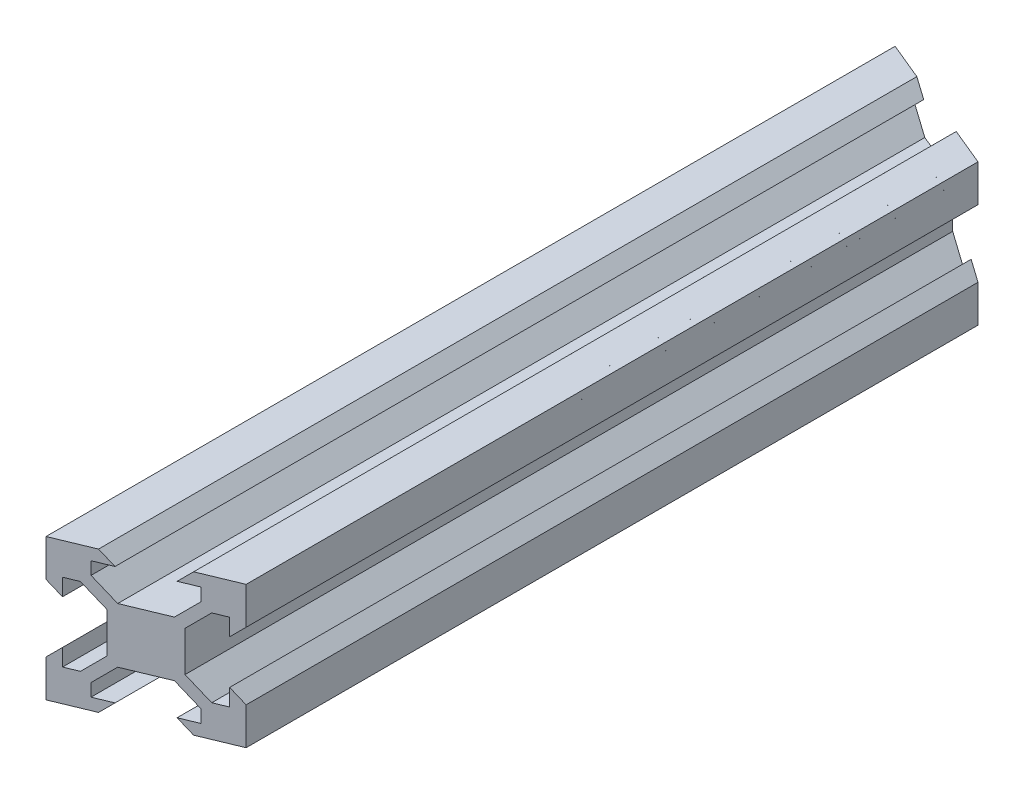
SolidWorks part; units mm, degrees
material "6061 Alloy"
ref_plane "Front Plane" through (0, 0, 0) normal (0, 0, 1) x (1, 0, 0)
ref_plane "Top Plane" through (0, 0, 0) normal (0, 1, 0) x (1, 0, 0)
ref_plane "Right Plane" through (0, 0, 0) normal (1, 0, 0) x (0, 0, -1)
sketch "Sketch1" plane through (0, 0, 0) normal (0, 0, 1) x (1, 0, 0)
  line L4 (-2.8343, 3.894) -> (2.8343, 3.894)
  line L6 (2.8343, 3.894) -> (5.5, 6.5588)
  line L7 (5.5, 6.5588) -> (5.5, 8.3491)
  line L8 (5.5, 8.3491) -> (3.1, 8.3491)
  line L11 (3.1, 8.3491) -> (4.75, 9.9986)
  line L12 (4.75, 9.9986) -> (10, 9.9986)
  line L14 (10, 9.9986) -> (10, 4.747)
  line L16 (10, 4.747) -> (8.35, 3.0975)
  line L17 (8.35, 3.0975) -> (8.3507, 5.4975)
  line L18 (8.3507, 5.4975) -> (6.5605, 5.498)
  line L19 (6.5605, 5.498) -> (3.8948, 2.8332)
  line L20 (3.8948, 2.8332) -> (3.8948, -2.8332)
  line L22 (-10, 9.9986) -> (-10, 4.747)
  line L23 (-3.8948, 2.8332) -> (-3.8948, -2.8332)
  line L24 (-6.5605, 5.498) -> (-3.8948, 2.8332)
  line L25 (-8.3507, 5.4975) -> (-6.5605, 5.498)
  line L26 (-8.35, 3.0975) -> (-8.3507, 5.4975)
  line L27 (-10, 4.747) -> (-8.35, 3.0975)
  line L28 (-4.75, 9.9986) -> (-10, 9.9986)
  line L29 (-3.1, 8.3491) -> (-4.75, 9.9986)
  line L30 (-5.5, 8.3491) -> (-3.1, 8.3491)
  line L31 (-5.5, 6.5588) -> (-5.5, 8.3491)
  line L32 (-2.8343, 3.894) -> (-5.5, 6.5588)
  line L33 (-2.8343, -3.894) -> (-5.5, -6.5588)
  line L34 (-5.5, -6.5588) -> (-5.5, -8.3491)
  line L35 (-5.5, -8.3491) -> (-3.1, -8.3491)
  line L36 (-3.1, -8.3491) -> (-4.75, -9.9986)
  line L37 (-4.75, -9.9986) -> (-10, -9.9986)
  line L38 (-10, -4.747) -> (-8.35, -3.0975)
  line L39 (-8.35, -3.0975) -> (-8.3507, -5.4975)
  line L40 (-8.3507, -5.4975) -> (-6.5605, -5.498)
  line L41 (-6.5605, -5.498) -> (-3.8948, -2.8332)
  line L42 (-10, -9.9986) -> (-10, -4.747)
  line L43 (6.5605, -5.498) -> (3.8948, -2.8332)
  line L44 (8.3507, -5.4975) -> (6.5605, -5.498)
  line L45 (8.35, -3.0975) -> (8.3507, -5.4975)
  line L46 (10, -4.747) -> (8.35, -3.0975)
  line L47 (10, -9.9986) -> (10, -4.747)
  line L48 (4.75, -9.9986) -> (10, -9.9986)
  line L49 (3.1, -8.3491) -> (4.75, -9.9986)
  line L50 (5.5, -8.3491) -> (3.1, -8.3491)
  line L51 (5.5, -6.5588) -> (5.5, -8.3491)
  line L52 (2.8343, -3.894) -> (5.5, -6.5588)
  line L53 (-2.8343, -3.894) -> (2.8343, -3.894)
  circle A0 centre (0, 0) radius 2.1
  point P52 (0, 3.894)
  point P53 (-3.8948, 0)
  point P54 (3.8948, 0)
  point P74 (0, -3.894)
extrude "Boss-Extrude1" add sketch "Sketch1" along normal blind 120 contours L14 L16 L17 L18 L19 L20 L43 L44 L45 L46 L47 L48 L49 L50 L51 L52 L53 L33 L34 L35 L36 L37 L42 L38 L39 L40 L41 L23 L24 L25 L26 L27 L22 L28 L29 L30 L31 L32 L4 L6 L7 L8 L11 L12
sketch "Sketch2" plane through (0, 9.9986, 0) normal (0, 1, 0) x (1, 0, 0)
  line L0 (-10, -120) -> (10, -111.7157)
  line L1 (10, -120) -> (10, 0) construction
  line L2 (-2.8343, -120) -> (2.8343, -120) construction
  line L3 (10, -111.7157) -> (10, -120)
  line L4 (10, -120) -> (-10, -120)
  dimension "D1" = 22.5
extrude "Cut-Extrude1" cut sketch "Sketch2" against normal through all
sketch "Sketch3" plane through (0, 9.9986, 0) normal (0, 1, 0) x (1, 0, 0)
  line L0 (-10, 0) -> (10, -8.2843)
  line L1 (10, -111.7157) -> (10, 0) construction
  line L2 (10, -8.2843) -> (10, 0)
  line L3 (10, 0) -> (-10, 0)
  dimension "D1" = 22.5
extrude "Cut-Extrude2" cut sketch "Sketch3" against normal through all
